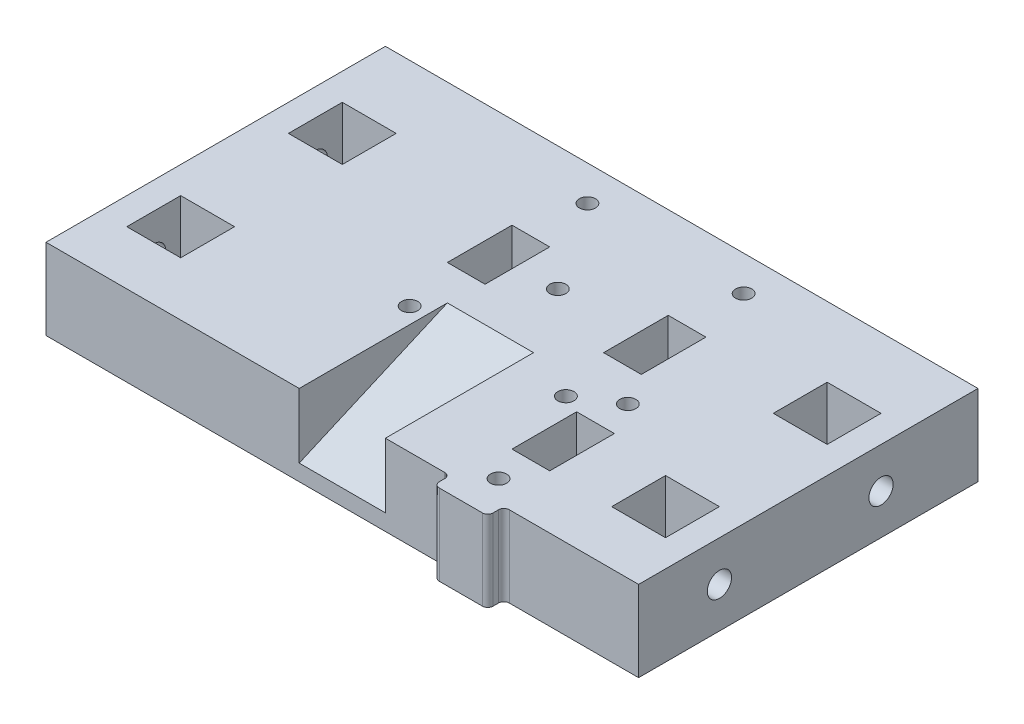
SolidWorks part; units mm, degrees
ref_plane "Alzado" through (0, 0, 0) normal (0, 0, 1) x (1, 0, 0)
ref_plane "Planta" through (0, 0, 0) normal (0, 1, 0) x (1, 0, 0)
ref_plane "Vista lateral" through (0, 0, 0) normal (1, 0, 0) x (0, 0, -1)
sketch "Croquis1" plane through (0, 0, 0) normal (0, 1, 0) x (1, 0, 0)
  line L0 (-50, 0) -> (55, 0) construction
  line L1 (0, 7.75) -> (-6.7117, 3.875)
  line L2 (-6.7117, 3.875) -> (-6.7117, -3.875)
  line L3 (-6.7117, -3.875) -> (0, -7.75)
  line L4 (0, -7.75) -> (6.7117, -3.875)
  line L5 (6.7117, -3.875) -> (6.7117, 3.875)
  line L6 (6.7117, 3.875) -> (0, 7.75)
  line L7 (-50, 20) -> (50, 20) construction
  line L8 (-50, -40) -> (50, -40) construction
  line L9 (-50, 10) -> (50, 10) construction
  line L10 (-50, 20) -> (-40, 20)
  line L11 (-50, 20) -> (-50, -40)
  line L12 (-50, -40) -> (-40, -40)
  line L13 (-40, 20) -> (-40, -40)
  line L14 (50, 20) -> (40, 20)
  line L15 (50, 20) -> (50, -40)
  line L16 (50, -40) -> (40, -40)
  line L17 (40, 20) -> (40, -40)
  line L18 (-40, 20) -> (40, 20)
  line L19 (-40, 20) -> (-40, -40)
  line L20 (-40, -40) -> (40, -40)
  line L21 (40, 20) -> (40, -40)
  line L22 (-50, -20) -> (50, -20) construction
  line L23 (-50, -30) -> (50, -30) construction
  line L24 (-14.5, 12.5) -> (21.5, 12.5) construction
  line L25 (-50, 10) -> (-40, 10)
  line L26 (-50, 10) -> (-50, 0)
  line L27 (-50, 0) -> (-40, 0)
  line L28 (-40, 10) -> (-40, 0)
  line L29 (50, 10) -> (40, 10)
  line L30 (50, 10) -> (50, 0)
  line L31 (50, 0) -> (40, 0)
  line L32 (40, 10) -> (40, 0)
  line L33 (50, -20) -> (40, -20)
  line L34 (50, -20) -> (50, -30)
  line L35 (50, -30) -> (40, -30)
  line L36 (40, -20) -> (40, -30)
  line L37 (-50, -20) -> (-40, -20)
  line L38 (-50, -20) -> (-50, -30)
  line L39 (-50, -30) -> (-40, -30)
  line L40 (-40, -20) -> (-40, -30)
  line L41 (-50, 20) -> (-55, 20)
  line L42 (-50, 20) -> (-50, -40)
  line L43 (-50, -40) -> (-55, -40)
  line L44 (-55, 20) -> (-55, -40)
  line L45 (50, 20) -> (55, 20)
  line L46 (50, 20) -> (50, -40)
  line L47 (50, -40) -> (55, -40)
  line L48 (55, 20) -> (55, -40)
  line L49 (-14.5, -12.5) -> (21.5, -12.5) construction
  line L50 (-11, 12.5) -> (-11, -12.5) construction
  line L51 (-14.5, 12.5) -> (-7.5, 12.5)
  line L52 (-14.5, 12.5) -> (-14.5, -12.5)
  line L53 (-14.5, -12.5) -> (-7.5, -12.5)
  line L54 (-7.5, 12.5) -> (-7.5, -12.5)
  line L55 (21.5, 12.5) -> (14.5, 12.5)
  line L56 (21.5, 12.5) -> (21.5, -12.5)
  line L57 (21.5, -12.5) -> (14.5, -12.5)
  line L58 (14.5, 12.5) -> (14.5, -12.5)
  line L59 (-14.5, 6) -> (-7.5, 6)
  line L60 (-14.5, 6) -> (-14.5, -6)
  line L61 (-14.5, -6) -> (-7.5, -6)
  line L62 (-7.5, 6) -> (-7.5, -6)
  line L63 (14.5, 6) -> (21.5, 6)
  line L64 (14.5, 6) -> (14.5, -6)
  line L65 (14.5, -6) -> (21.5, -6)
  line L66 (21.5, 6) -> (21.5, -6)
  line L67 (18, 12.5) -> (18, -12.5) construction
  circle A0 centre (0, 0) radius 7.75 construction
  circle A1 centre (-11, 16.5) radius 1.5
  circle A2 centre (18, 16.5) radius 1.5
  circle A3 centre (-11, -16.5) radius 1.5
  circle A4 centre (18, -16.5) radius 1.5
  dimension "D1" = 15.5
  dimension "D24" = 3
  dimension "D25" = 3
  dimension "D26" = 3
  dimension "D27" = 3
  dimension "D2" = 100
  dimension "D3" = 10
  dimension "D4" = 10
  dimension "D5" = 20
  dimension "D6" = 50
  dimension "D7" = 60
  dimension "D8" = 10
  dimension "D9" = 20
  dimension "D10" = 10
  dimension "D11" = 5
  dimension "D12" = 5
  dimension "D13" = 40
  dimension "D14" = 7
  dimension "D15" = 7
  dimension "D16" = 25
  dimension "D17" = 12.5
  dimension "D18" = 7.5
  dimension "D19" = 14.5
  dimension "D20" = 12
  dimension "D21" = 12
  dimension "D22" = 6.5
  dimension "D23" = 6.5
  dimension "D28" = 4
  dimension "D29" = 4
  dimension "D30" = 4
  dimension "D31" = 4
  dimension "D32" = 3.5
  dimension "D33" = 3.5
  dimension "D34" = 3.5
  dimension "D35" = 3.5
extrude "Saliente-Extruir1" add sketch "Croquis1" along normal blind 15 contours L13 L19 L20 L17 L21 L18 A4 A3 A2 A1 L58 L55 L56 L57 L6 L5 L4 L3 L2 L1 L51 L54 L53 L52 | L11 L37 L13 L27 | L39 L11 L12 L13 | L41 L44 L43 L11 | L11 L25 L13 L10 | L29 L15 L14 L17 | L48 L45 L15 L47 | L33 L15 L31 L17 | L15 L35 L17 L16 | L52 L59 L54 L51 | L61 L52 L53 L54 | L58 L63 L56 L55 | L65 L58 L57 L56
sketch "Croquis2" plane through (0, 0, 0) normal (0, -1, 0) x (1, 0, 0)
  line L1 (-7.3916, 16.5) -> (-9.1958, 19.625)
  line L2 (-9.1958, 19.625) -> (-12.8042, 19.625)
  line L3 (-12.8042, 19.625) -> (-14.6084, 16.5)
  line L4 (-14.6084, 16.5) -> (-12.8042, 13.375)
  line L5 (-12.8042, 13.375) -> (-9.1958, 13.375)
  line L6 (-9.1958, 13.375) -> (-7.3916, 16.5)
  line L7 (21.6084, 16.5) -> (19.8042, 19.625)
  line L8 (19.8042, 19.625) -> (16.1958, 19.625)
  line L9 (16.1958, 19.625) -> (14.3916, 16.5)
  line L10 (14.3916, 16.5) -> (16.1958, 13.375)
  line L11 (16.1958, 13.375) -> (19.8042, 13.375)
  line L12 (19.8042, 13.375) -> (21.6084, 16.5)
  line L13 (-7.3916, -16.5) -> (-9.1958, -13.375)
  line L14 (-9.1958, -13.375) -> (-12.8042, -13.375)
  line L15 (-12.8042, -13.375) -> (-14.6084, -16.5)
  line L16 (-14.6084, -16.5) -> (-12.8042, -19.625)
  line L17 (-12.8042, -19.625) -> (-9.1958, -19.625)
  line L18 (-9.1958, -19.625) -> (-7.3916, -16.5)
  line L19 (21.6084, -16.5) -> (19.8042, -13.375)
  line L20 (19.8042, -13.375) -> (16.1958, -13.375)
  line L21 (16.1958, -13.375) -> (14.3916, -16.5)
  line L22 (14.3916, -16.5) -> (16.1958, -19.625)
  line L23 (16.1958, -19.625) -> (19.8042, -19.625)
  line L24 (19.8042, -19.625) -> (21.6084, -16.5)
  circle A0 centre (-11, 16.5) radius 3.125 construction
  circle A1 centre (18, 16.5) radius 3.125 construction
  circle A2 centre (-11, -16.5) radius 3.125 construction
  circle A3 centre (18, -16.5) radius 3.125 construction
extrude "Cortar-Extruir1" cut sketch "Croquis2" against normal blind 10
sketch "Croquis3" plane through (55, 0, 0) normal (1, 0, 0) x (0, 0, -1)
  line L0 (-40, 7.5) -> (20, 7.5) construction
  line L1 (-40, 15) -> (-40, 0) construction
  line L2 (20, 15) -> (20, 0) construction
  circle A0 centre (-25, 7.5) radius 1.5
  circle A1 centre (5, 7.5) radius 1.5
  dimension "D3" = 3
  dimension "D4" = 3
  dimension "D1" = 15
  dimension "D2" = 15
extrude "Cortar-Extruir2" cut sketch "Croquis3" against normal blind 25
sketch "Croquis6" plane through (-55, 0, 0) normal (-1, 0, 0) x (0, 0, 1)
  line L0 (-20, 7.5) -> (40, 7.5) construction
  line L1 (-20, 15) -> (-20, 0) construction
  line L2 (40, 15) -> (40, 0) construction
  circle A0 centre (-5, 7.5) radius 1.5
  circle A1 centre (25, 7.5) radius 1.5
  dimension "D1" = 3
  dimension "D2" = 3
  dimension "D3" = 15
  dimension "D4" = 15
extrude "Cortar-Extruir3" cut sketch "Croquis6" against normal blind 25
sketch "Croquis8" plane through (0, 15, 0) normal (0, 1, 0) x (1, 0, 0)
  line L0 (-7.5, 6) -> (-7.5, -6) construction
  line L1 (7.5, -8.9193) -> (-7.5, -8.9193)
  line L2 (7.5, -8.9193) -> (7.5, 8.9193)
  line L3 (7.5, 8.9193) -> (-7.5, 8.9193)
  line L4 (-7.5, -8.9193) -> (-7.5, 8.9193)
  line L5 (7.5, -8.9193) -> (-7.5, 8.9193) construction
  line L6 (7.5, 8.9193) -> (-7.5, -8.9193) construction
  circle A0 centre (0, 0) radius 1.5
  point P0 (0, 0)
  dimension "D1" = 3
extrude "Saliente-Extruir2" add sketch "Croquis8" against normal blind 5
sketch "Croquis9" plane through (55, 0, 0) normal (1, 0, 0) x (0, 0, -1)
  line L0 (-12.5, 15) -> (-40, 3)
  line L1 (-40, 15) -> (0, 15)
  line L2 (-40, 15) -> (-40, 0)
  line L3 (-40, 0) -> (0, 0)
  line L4 (0, 15) -> (0, 0)
  circle M5 centre (-25, 7.5) radius 1.5
  line M7 (-40, 0) -> (20, 0)
  line M9 (20, 15) -> (-40, 15)
  line M10 (-40, 15) -> (-40, 0)
  dimension "D1" = 12.5
  dimension "D2" = 3
extrude "Cortar-Extruir4" cut sketch "Croquis9" against normal mid plane 16 from offset 55 contours L4 L0 M9 M10 M7 M5 offset against normal yes
sketch "Croquis10" plane through (0, 15, 0) normal (0, 1, 0) x (1, 0, 0)
  line L0 (25, 20) -> (25, -40) construction
  line L1 (-55, 20) -> (55, 20) construction
  line L2 (8, -40) -> (55, -40) construction
  line L4 (21.5, -30) -> (28.5, -30)
  line L5 (21.5, -30) -> (21.5, -18)
  line L6 (21.5, -18) -> (28.5, -18)
  line L7 (28.5, -30) -> (28.5, -18)
  line L8 (21.5, -30) -> (28.5, -18) construction
  line L9 (21.5, -18) -> (28.5, -30) construction
  circle A0 centre (25, -12) radius 1.5
  circle A1 centre (25, -36) radius 1.5
  point P6 (25, -24)
  dimension "D5" = 3
  dimension "D6" = 3
  dimension "D1" = 25
  dimension "D2" = 7
  dimension "D3" = 12
  dimension "D4" = 24
  dimension "D7" = 6
  dimension "D8" = 6
extrude "Cortar-Extruir5" cut sketch "Croquis10" against normal blind 16
sketch "Croquis12" plane through (0, 0, -20) normal (0, 0, -1) x (-1, 0, 0)
  line L1 (-55, 15) -> (55, 15)
  line L2 (-55, 15) -> (-55, 0)
  line L3 (-55, 0) -> (55, 0)
  line L4 (55, 15) -> (55, 0)
extrude "Saliente-Extruir3" add sketch "Croquis12" along normal blind 3
sketch "Croquis13" plane through (0, 0, 0) normal (0, -1, 0) x (1, 0, 0)
  line L1 (28.6084, 12) -> (26.8042, 15.125)
  line L2 (26.8042, 15.125) -> (23.1958, 15.125)
  line L3 (23.1958, 15.125) -> (21.3916, 12)
  line L4 (21.3916, 12) -> (23.1958, 8.875)
  line L5 (23.1958, 8.875) -> (26.8042, 8.875)
  line L6 (26.8042, 8.875) -> (28.6084, 12)
  line L7 (28.6084, 36) -> (26.8042, 39.125)
  line L8 (26.8042, 39.125) -> (23.1958, 39.125)
  line L9 (23.1958, 39.125) -> (21.3916, 36)
  line L10 (21.3916, 36) -> (23.1958, 32.875)
  line L11 (23.1958, 32.875) -> (26.8042, 32.875)
  line L12 (26.8042, 32.875) -> (28.6084, 36)
  circle A0 centre (25, 12) radius 3.125 construction
  circle A1 centre (25, 36) radius 3.125 construction
extrude "Cortar-Extruir6" cut sketch "Croquis13" against normal blind 10
sketch "Croquis14" plane through (0, 0, 0) normal (0, -1, 0) x (1, 0, 0)
  line L0 (-55, 40) -> (55, 40) construction
  line L2 (30, 41) -> (30, 42)
  line L3 (29, 43) -> (21, 43)
  line L4 (20, 41) -> (20, 42)
  line L5 (19, 40) -> (31, 40)
  circle A0 centre (25, 36) radius 1.5 construction
  arc A1 (30, 42) -> (29, 43) centre (29, 42) ccw
  arc A2 (21, 43) -> (20, 42) centre (21, 42) ccw
  arc A3 (20, 41) -> (19, 40) centre (19, 41) cw
  arc A4 (31, 40) -> (30, 41) centre (31, 41) cw
  dimension "D4" = 1
  dimension "D5" = 1
  dimension "D1" = 3
  dimension "D2" = 5
  dimension "D3" = 5
extrude "Saliente-Extruir4" add sketch "Croquis14" against normal blind 15
sketch "Croquis15" plane through (55, 0, 0) normal (1, 0, 0) x (0, 0, -1)
  circle A0 centre (-25, 7.5) radius 2.25
  circle A1 centre (5, 7.5) radius 2.25
  dimension "D1" = 4.5
  dimension "D2" = 4.5
extrude "Cortar-Extruir7" cut sketch "Croquis15" against normal blind 10
sketch "Croquis16" plane through (-55, 0, 0) normal (-1, 0, 0) x (0, 0, 1)
  circle A0 centre (-5, 7.5) radius 2.25
  circle A1 centre (25, 7.5) radius 2.25
  dimension "D1" = 4.5
  dimension "D2" = 4.5
extrude "Cortar-Extruir8" cut sketch "Croquis16" against normal blind 10
